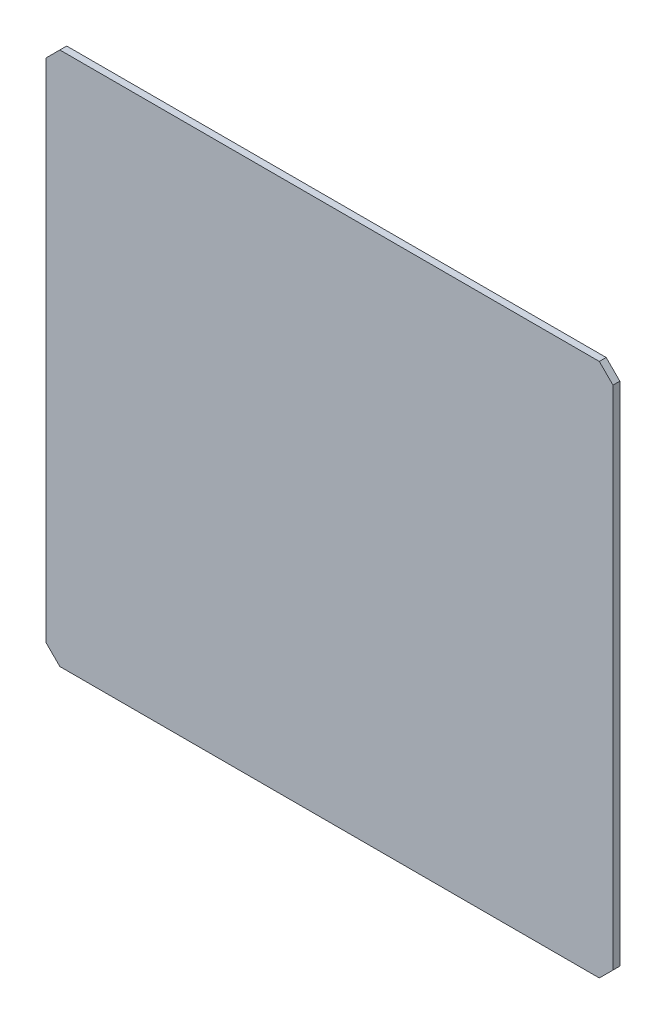
SolidWorks part; units mm, degrees
material "Acrilico (impatto medio-alto)"
ref_plane "Piano frontale" through (0, 0, 0) normal (0, 0, 1) x (1, 0, 0)
ref_plane "Piano superiore" through (0, 0, 0) normal (0, 1, 0) x (1, 0, 0)
ref_plane "Piano destro" through (0, 0, 0) normal (1, 0, 0) x (0, 0, -1)
sketch "Schizzo1" plane through (0, 0, 0) normal (0, 0, 1) x (1, 0, 0)
  line L0 (-207, 185) -> (-197, 195)
  line L1 (197, -195) -> (-197, -195)
  line L2 (207, -185) -> (207, 185)
  line L3 (197, 195) -> (-197, 195)
  line L4 (-207, -185) -> (-207, 185)
  line L5 (207, -195) -> (-207, 195) construction
  line L6 (207, 195) -> (-207, -195) construction
  line L7 (207, 185) -> (197, 195)
  line L8 (197, -195) -> (207, -185)
  line L9 (-197, -195) -> (-207, -185)
  point P0 (0, 0)
  dimension "D1" = 414
  dimension "D2" = 390
extrude "Estrusione-Estrusione1" add sketch "Schizzo1" along normal blind 5 contours L4 L0 L3 L7 L2 L8 L1 L9
